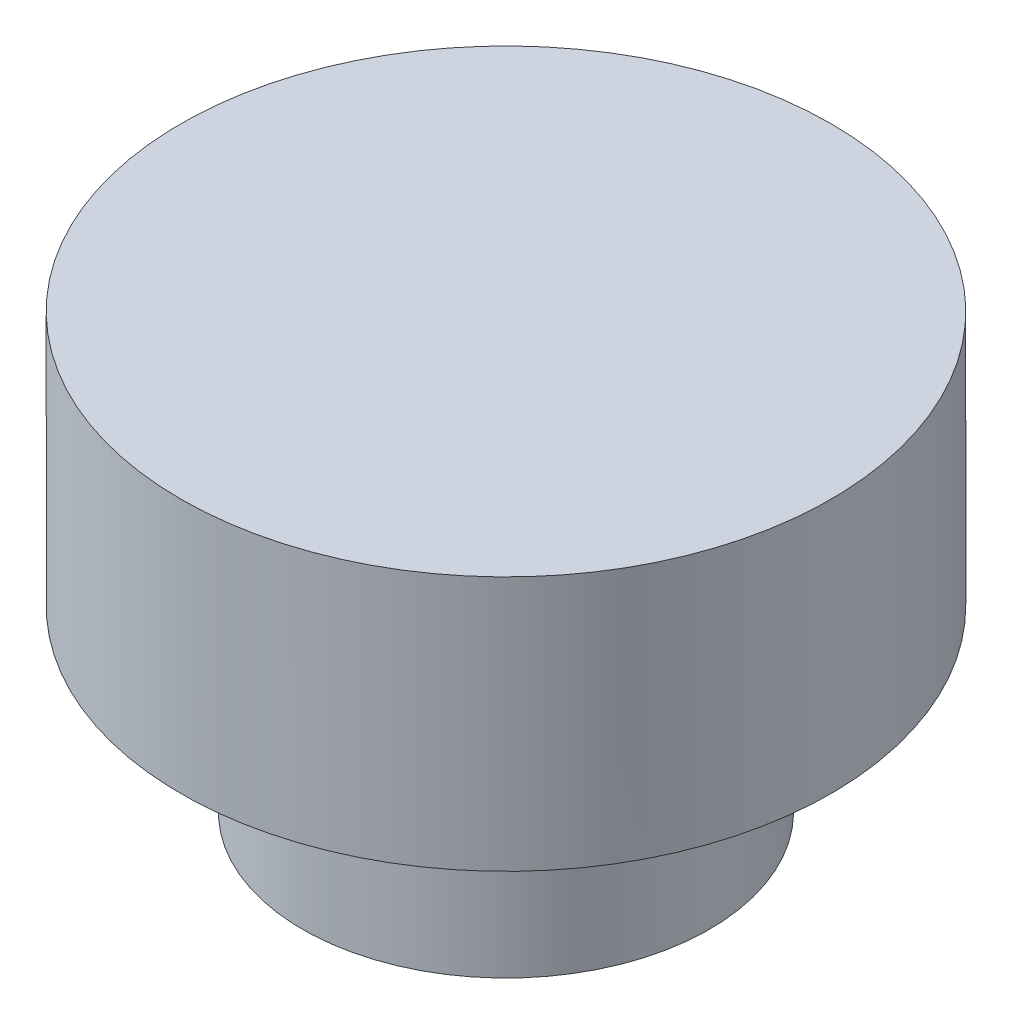
SolidWorks part; units mm, degrees
ref_plane "Front Plane" through (0, 0, 0) normal (0, 0, 1) x (1, 0, 0)
ref_plane "Top Plane" through (0, 0, 0) normal (0, 1, 0) x (1, 0, 0)
ref_plane "Right Plane" through (0, 0, 0) normal (1, 0, 0) x (0, 0, -1)
sketch "Sketch1" plane through (0, 0, 0) normal (0, 1, 0) x (1, 0, 0)
  circle A0 centre (0, 0) radius 12.75
  dimension "D1" = 25.5
extrude "Boss-Extrude1" add sketch "Sketch1" along normal blind 17
sketch "Sketch2" plane through (0, 0, 0) normal (0, -1, 0) x (1, 0, 0)
  circle A0 centre (0, 0) radius 12.75
  circle A1 centre (0, 0) radius 7.975
  dimension "D1" = 15.95
  dimension "D2" = 25.5
extrude "Cut-Extrude1" cut sketch "Sketch2" against normal blind 7
